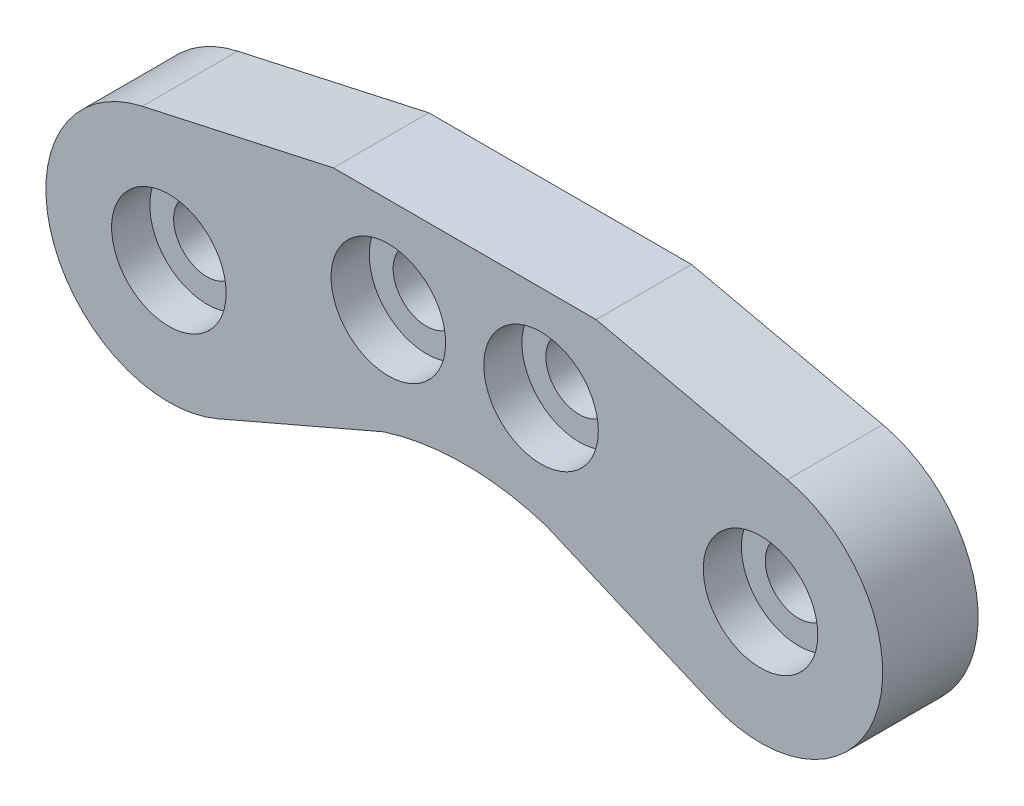
SolidWorks part; units mm, degrees
material "ABS"
ref_plane "Front Plane" through (0, 0, 0) normal (0, 0, 1) x (1, 0, 0)
ref_plane "Top Plane" through (0, 0, 0) normal (0, 1, 0) x (1, 0, 0)
ref_plane "Right Plane" through (0, 0, 0) normal (1, 0, 0) x (0, 0, -1)
sketch "Sketch1" plane through (0, 0, 0) normal (0, 0, 1) x (1, 0, 0)
  line L0 (23.1168, 8) -> (36.8832, 8)
  line L1 (25.7556, -2.6589) -> (17.0541, -6.4157)
  line L2 (34.2444, -2.6589) -> (42.9891, -6.388)
  line L3 (13.1115, 5.7922) -> (23.1168, 8)
  line L4 (46.9052, 5.7448) -> (36.8832, 8)
  arc A0 (13.1115, 5.7922) -> (17.0541, -6.4157) centre (14.5, -0.5) ccw
  arc A1 (42.9891, -6.388) -> (46.9052, 5.7448) centre (45.5, -0.5) ccw
  arc A2 (34.2444, -2.6589) -> (25.7556, -2.6589) centre (30, -16) ccw
extrude "Boss-Extrude1" add sketch "Sketch1" along normal blind 5
sketch "Sketch2" plane through (0, 0, 5) normal (0, 0, 1) x (1, 0, 0)
  circle A1 centre (45.5, -0.5) radius 1.75
  circle A2 centre (14.5, -0.5) radius 1.75
  circle A3 centre (26, 3) radius 1.75
  circle A4 centre (34, 3) radius 1.75
  dimension "D4" = 3.5
  dimension "D1" = 11.5
  dimension "D2" = 8
  dimension "D3" = 3.5
extrude "Cut-Extrude1" cut sketch "Sketch2" against normal through all both and the other way through all
sketch "Sketch5" plane through (0, 0, 5) normal (0, 0, 1) x (1, 0, 0)
  circle A0 centre (26, 3) radius 3
  circle A1 centre (34, 3) radius 3
  circle A2 centre (45.5, -0.5) radius 3
  circle A3 centre (14.5, -0.5) radius 3
  dimension "D1" = 6
extrude "Cut-Extrude2" cut sketch "Sketch5" against normal blind 2
equation "\"D1@Sketch2\"=(31-8)/2"
